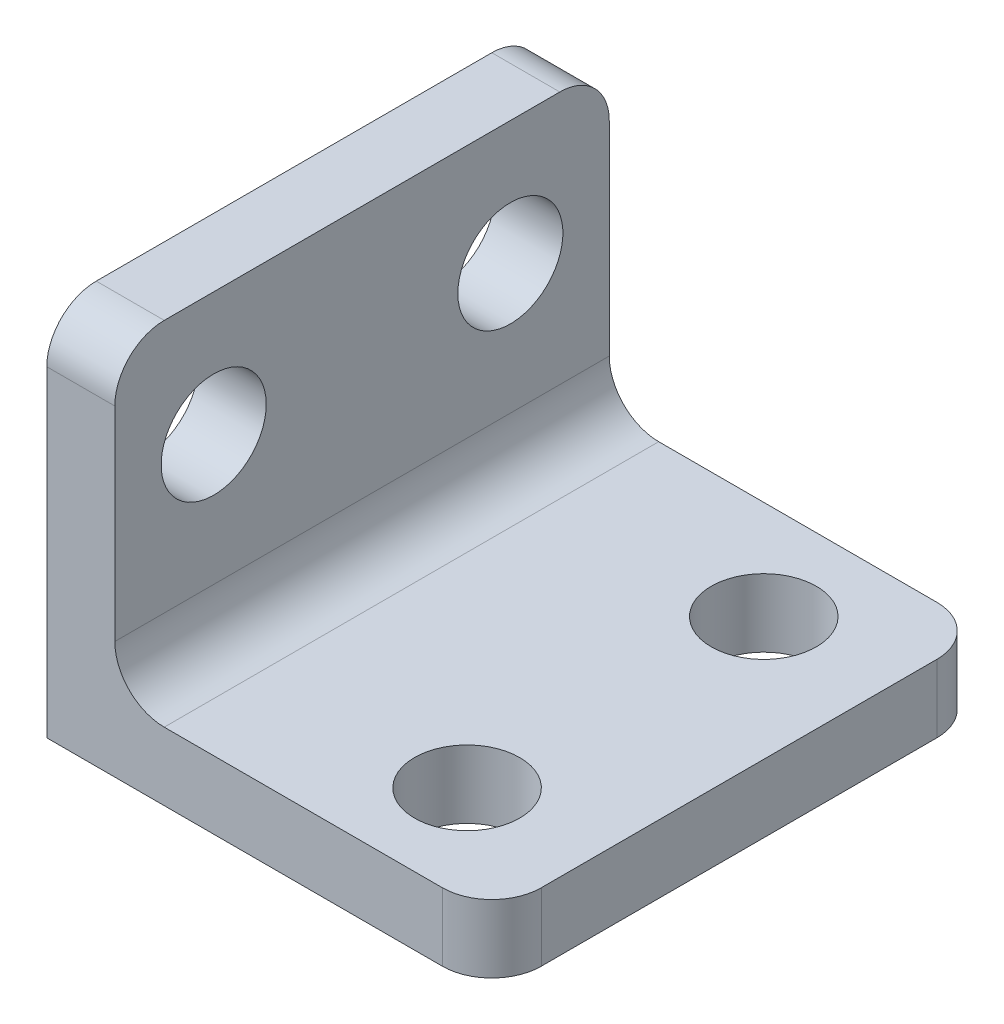
SolidWorks part; units mm, degrees
ref_plane "Front Plane" through (0, 0, 0) normal (0, 0, 1) x (1, 0, 0)
ref_plane "Top Plane" through (0, 0, 0) normal (0, 1, 0) x (1, 0, 0)
ref_plane "Right Plane" through (0, 0, 0) normal (1, 0, 0) x (0, 0, -1)
sketch "Sketch3" plane through (0, 0, 0) normal (0, 1, 0) x (1, 0, 0)
  line L0 (-3, -10) -> (15, -10)
  line L1 (0, 0) -> (15, 0) construction
  line L3 (-3, 10) -> (15, 10)
  line L4 (15, -10) -> (15, 10)
  line L5 (-3, 10) -> (-3, -10)
  circle A0 centre (10, 6) radius 2.125
  circle A1 centre (10, -6) radius 2.125
  dimension "D2" = 4.25
  dimension "D1" = 6
  dimension "D3" = 10
  dimension "D4" = 13
  dimension "D5" = 5
extrude "Boss-Extrude3" add sketch "Sketch3" along normal blind 2.75
sketch "Sketch5" plane through (-3, 0, 0) normal (-1, 0, 0) x (0, 0, 1)
  line L0 (0, 15) -> (0, 0.1839) construction
  line L1 (-10, 0) -> (10, 0)
  line L2 (-10, 0) -> (-10, 15)
  line L3 (-10, 15) -> (10, 15)
  line L4 (10, 0) -> (10, 15)
  circle A0 centre (-6, 10) radius 2.125
  circle A1 centre (6, 10) radius 2.125
  dimension "D1" = 4.25
  dimension "D2" = 5
  dimension "D3" = 6
  dimension "D4" = 10
extrude "Boss-Extrude5" add sketch "Sketch5" against normal blind 2.75
fillet "Fillet4" radius 2 5 edges at (15, 1.375, -10) (15, 1.375, 10) (-1.625, 15, -10) (-1.625, 15, 10) (-0.25, 2.75, 0)
